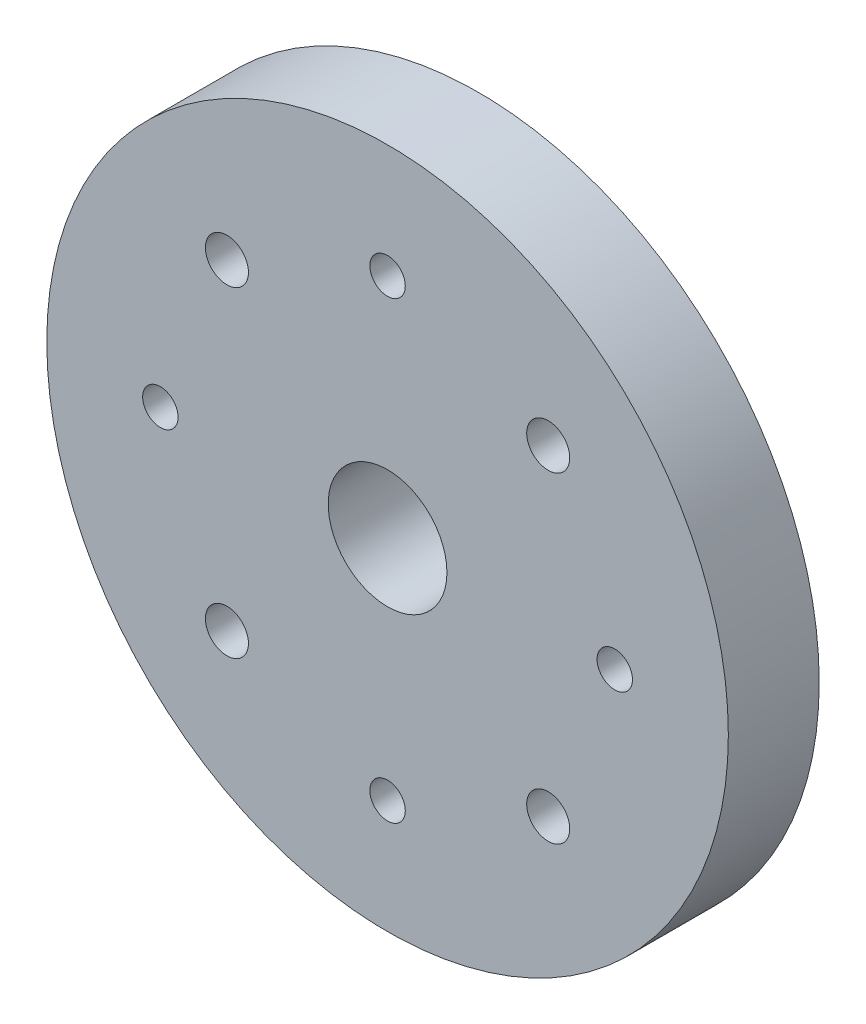
SolidWorks part; units mm, degrees
material "Balsa"
ref_plane "Front Plane" through (0, 0, 0) normal (0, 0, 1) x (1, 0, 0)
ref_plane "Top Plane" through (0, 0, 0) normal (0, 1, 0) x (1, 0, 0)
ref_plane "Right Plane" through (0, 0, 0) normal (1, 0, 0) x (0, 0, -1)
sketch "Sketch1" plane through (0, 0, 0) normal (0, 0, 1) x (1, 0, 0)
  circle A0 centre (0, 0) radius 22.5
  circle A1 centre (0, 0) radius 4
  circle A2 centre (0, 0) radius 15 construction
  circle A3 centre (0, 15) radius 1.25
  circle A4 centre (10.6066, 10.6066) radius 1.5
  circle A5 centre (15, 0) radius 1.25
  circle A6 centre (10.6066, -10.6066) radius 1.5
  circle A7 centre (0, -15) radius 1.25
  circle A8 centre (-10.6066, -10.6066) radius 1.5
  circle A9 centre (-15, 0) radius 1.25
  circle A10 centre (-10.6066, 10.6066) radius 1.5
  dimension "D1" = 45
  dimension "D2" = 8
  dimension "D3" = 30
  dimension "D4" = 2.5
  dimension "D5" = 3
  dimension "D6" = 45
extrude "Boss-Extrude1" add sketch "Sketch1" along normal blind 6
other "Move Face1" face at (4, 0, 6) face at (1.25, 15, 6) face at (12.1066, 10.6066, 6) face at (16.25, 0, 6) face at (12.1066, -10.6066, 6) face at (1.25, -15, 6) face at (-9.1066, -10.6066, 6) face at (-13.75, 0, 6) face at (-9.1066, 10.6066, 6) parameters "D1"=0.08
